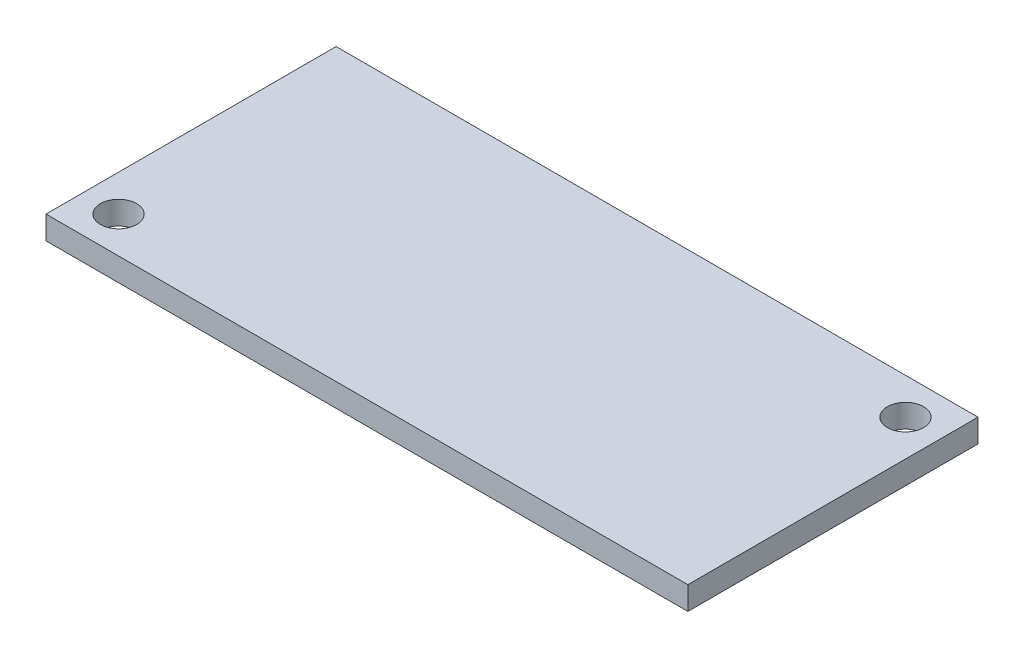
SolidWorks part; units mm, degrees
material "ABS"
ref_plane "Front Plane" through (0, 0, 0) normal (0, 0, 1) x (1, 0, 0)
ref_plane "Top Plane" through (0, 0, 0) normal (0, 1, 0) x (1, 0, 0)
ref_plane "Right Plane" through (0, 0, 0) normal (1, 0, 0) x (0, 0, -1)
sketch "Sketch1" plane through (0, 0, 0) normal (0, 1, 0) x (1, 0, 0)
  line L1 (-22.125, -10) -> (22.125, -10)
  line L2 (-22.125, -10) -> (-22.125, 10)
  line L3 (-22.125, 10) -> (22.125, 10)
  line L4 (22.125, -10) -> (22.125, 10)
  line L5 (-22.125, -10) -> (22.125, 10) construction
  line L6 (-22.125, 10) -> (22.125, -10) construction
  point P0 (0, 0)
  dimension "D1" = 44.25
  dimension "D2" = 20
extrude "Boss-Extrude1" add sketch "Sketch1" along normal blind 1.6
sketch "Sketch8" plane through (0, 1.6, 0) normal (0, 1, 0) x (1, 0, 0)
  line L0 (-22.125, 10) -> (-22.125, -10) construction
  line L1 (22.125, 10) -> (-22.125, 10) construction
  line L2 (-22.125, -10) -> (22.125, -10) construction
  line L3 (0, -10) -> (0, 10.0491) construction
  line L4 (-22.125, 0) -> (22.518, 0) construction
  line L5 (22.125, -10) -> (22.125, 10) construction
  circle A0 centre (-19.625, -7.5) radius 1.25
  circle A1 centre (19.625, 7.5) radius 1.25
  dimension "D1" = 2.5
  dimension "D2" = 2.5
  dimension "D3" = 2.5
  dimension "D4" = 2.5
  dimension "D5" = 2.5
extrude "Cut-Extrude3" cut sketch "Sketch8" against normal through all
